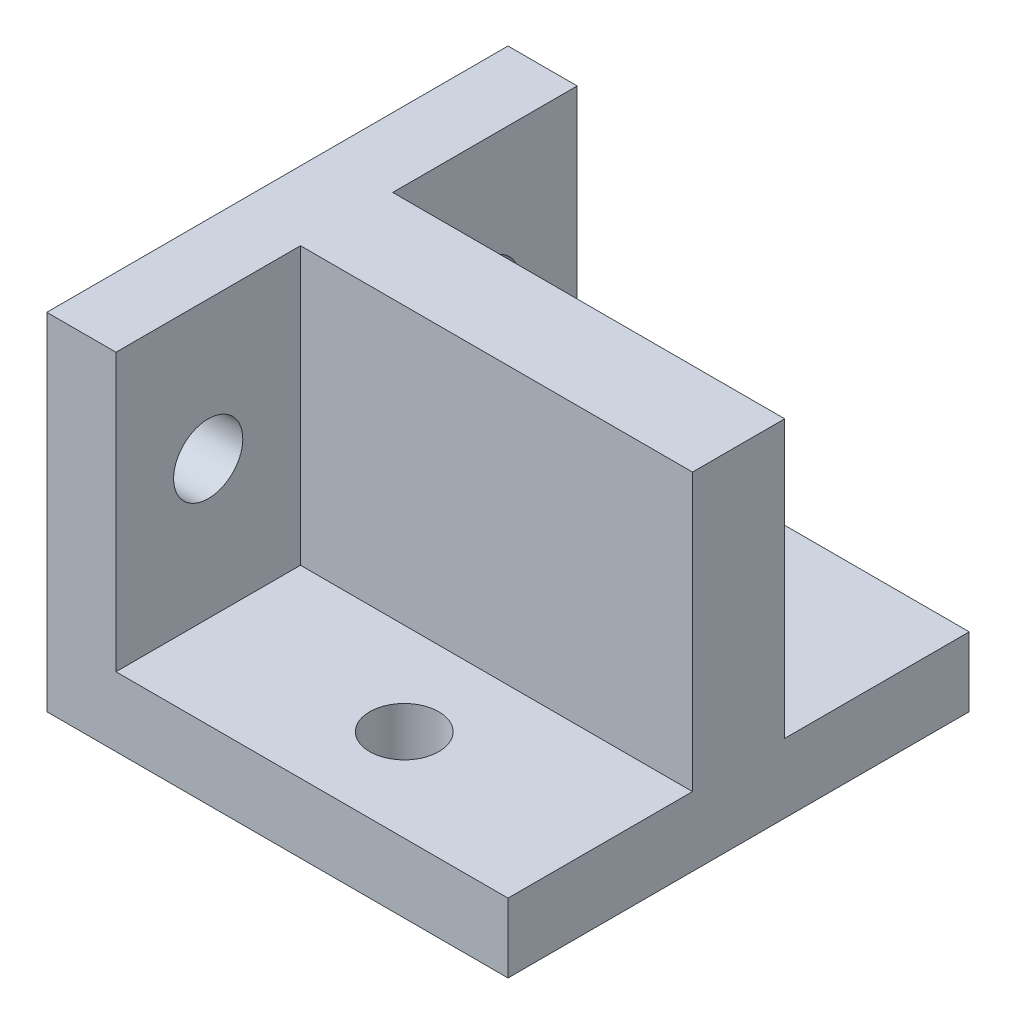
SolidWorks part; units mm, degrees
material "POM 乙缩醛共聚物"
ref_plane "前视基准面" through (0, 0, 0) normal (0, 0, 1) x (1, 0, 0)
ref_plane "上视基准面" through (0, 0, 0) normal (0, 1, 0) x (1, 0, 0)
ref_plane "右视基准面" through (0, 0, 0) normal (1, 0, 0) x (0, 0, -1)
sketch "草图1" plane through (0, 0, 0) normal (0, 0, 1) x (1, 0, 0)
  line L0 (0, 0) -> (0, 12)
  line L1 (0, 12) -> (-3, 12)
  line L2 (-3, 12) -> (-3, -3)
  line L3 (-3, -3) -> (17, -3)
  line L4 (17, -3) -> (17, 0)
  line L5 (17, 0) -> (0, 0)
  dimension "D1" = 3
  dimension "D2" = 20
  dimension "D3" = 15
extrude "凸台-拉伸1" add sketch "草图1" along normal blind 20
sketch "草图2" plane through (0, 0, 0) normal (1, 0, 0) x (0, 0, -1)
  line L0 (-20, 6) -> (0, 6) construction
  line L1 (-20, 0) -> (-20, 12) construction
  line L2 (0, 0) -> (0, 12) construction
  line L3 (-20, 12) -> (0, 12) construction
  line L4 (-10, 6) -> (-10, 12) construction
  circle A0 centre (-16, 6) radius 1.5
  circle A1 centre (-4, 6) radius 1.5
  dimension "D2" = 6
  dimension "D3" = 3
  dimension "D1" = 6
extrude "切除-拉伸1" cut sketch "草图2" against normal through all
sketch "草图3" plane through (0, 0, 0) normal (0, 1, 0) x (1, 0, 0)
  line L0 (8.5, -20) -> (8.5, 0) construction
  line L1 (17, -20) -> (0, -20) construction
  line L2 (17, 0) -> (0, 0) construction
  line L3 (8.5, -10) -> (17, -10) construction
  line L4 (17, -20) -> (17, 0) construction
  circle A0 centre (8.5, -16) radius 1.5
  circle A1 centre (8.5, -4) radius 1.5
  dimension "D1" = 8.5
  dimension "D3" = 3
  dimension "D2" = 6
extrude "切除-拉伸2" cut sketch "草图3" against normal through all
sketch "草图4" plane through (0, 0, 0) normal (1, 0, 0) x (0, 0, -1)
  line L0 (-20, 12) -> (0, 12) construction
  line L1 (-12, 12) -> (-8, 12)
  line L2 (-12, 12) -> (-12, 0)
  line L3 (-12, 0) -> (-8, 0)
  line L4 (-8, 12) -> (-8, 0)
  line L5 (-20, 0) -> (0, 0) construction
  point P8 (-10, 0)
  dimension "D1" = 4
extrude "凸台-拉伸2" add sketch "草图4" along normal up to surface (17 mm away) up to face at (17, -1.5, 10)
